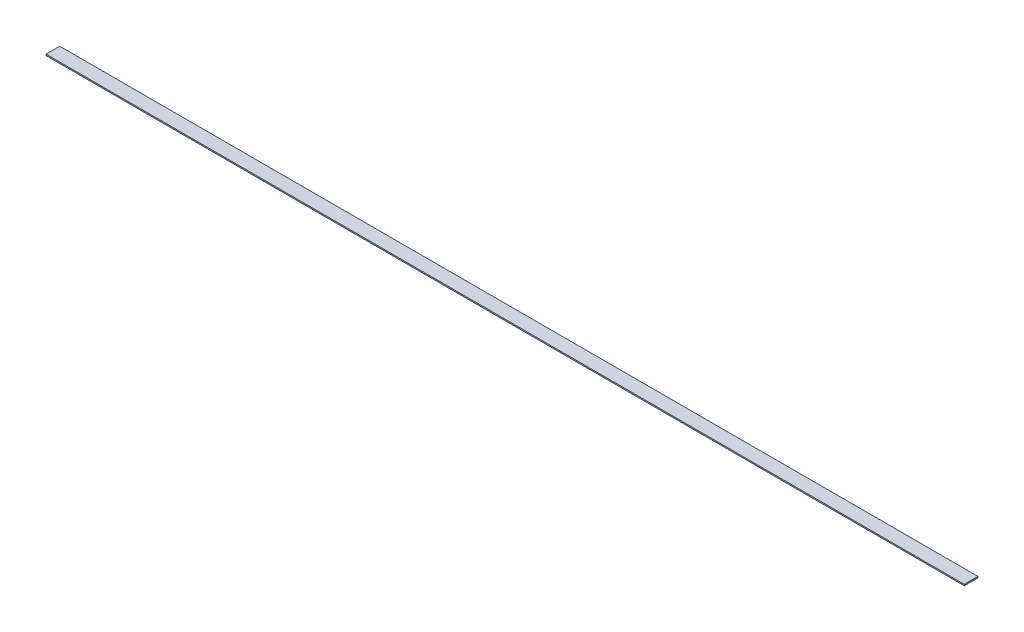
SolidWorks part; units mm, degrees
ref_plane "Front Plane" through (0, 0, 0) normal (0, 0, 1) x (1, 0, 0)
ref_plane "Top Plane" through (0, 0, 0) normal (0, 1, 0) x (1, 0, 0)
ref_plane "Right Plane" through (0, 0, 0) normal (1, 0, 0) x (0, 0, -1)
sketch "Sketch1" plane through (0, 0, 0) normal (0, 1, 0) x (1, 0, 0)
  line L1 (-1701.8, 25.4) -> (1701.8, 25.4)
  line L2 (-1701.8, 25.4) -> (-1701.8, -25.4)
  line L3 (-1701.8, -25.4) -> (1701.8, -25.4)
  line L4 (1701.8, 25.4) -> (1701.8, -25.4)
  line L5 (-1701.8, 25.4) -> (1701.8, -25.4) construction
  line L6 (-1701.8, -25.4) -> (1701.8, 25.4) construction
  point P0 (0, 0)
  dimension "D1" = 3403.6
  dimension "D2" = 50.8
extrude "Boss-Extrude1" add sketch "Sketch1" along normal blind 4.7625
